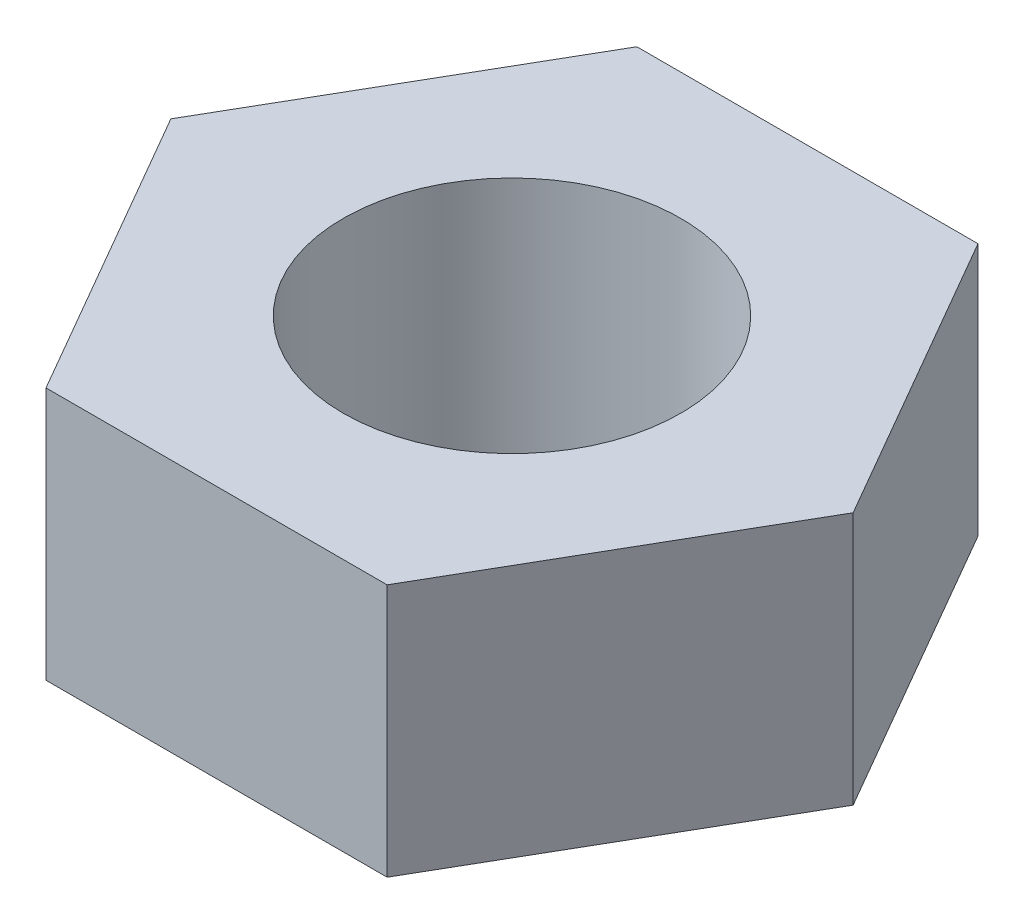
SolidWorks part; units mm, degrees
ref_plane "正面" through (0, 0, 0) normal (0, 0, 1) x (1, 0, 0)
ref_plane "平面" through (0, 0, 0) normal (0, 1, 0) x (1, 0, 0)
ref_plane "右側面" through (0, 0, 0) normal (1, 0, 0) x (0, 0, -1)
sketch "ｽｹｯﾁ1" plane through (0, 0, 0) normal (0, 1, 0) x (1, 0, 0)
  line L1 (2.0207, -3.5) -> (4.0415, 0)
  line L2 (4.0415, 0) -> (2.0207, 3.5)
  line L3 (2.0207, 3.5) -> (-2.0207, 3.5)
  line L4 (-2.0207, 3.5) -> (-4.0415, 0)
  line L5 (-4.0415, 0) -> (-2.0207, -3.5)
  line L6 (-2.0207, -3.5) -> (2.0207, -3.5)
  circle A0 centre (0, 0) radius 3.5 construction
  circle A1 centre (0, 0) radius 2
  point P1 (0, 3.5)
  dimension "D2" = 4
  dimension "D1" = 7
extrude "押し出し1" add sketch "ｽｹｯﾁ1" along normal blind 3
